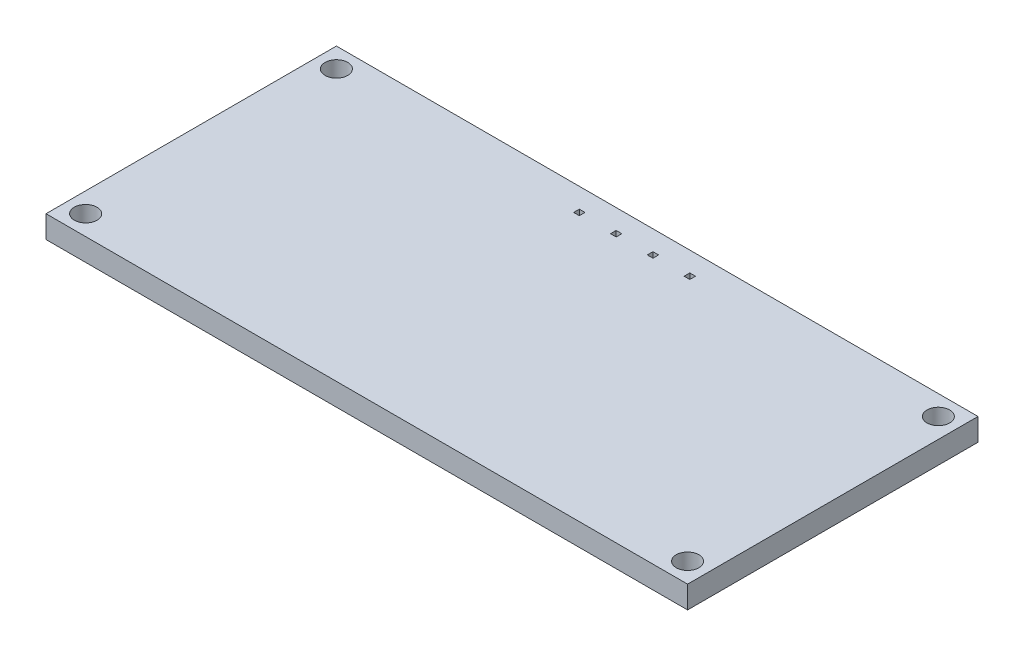
SolidWorks part; units mm, degrees
ref_plane "Alzado" through (0, 0, 0) normal (0, 0, 1) x (1, 0, 0)
ref_plane "Planta" through (0, 0, 0) normal (0, 1, 0) x (1, 0, 0)
ref_plane "Vista lateral" through (0, 0, 0) normal (1, 0, 0) x (0, 0, -1)
sketch "Croquis1" plane through (0, 0, 0) normal (0, 1, 0) x (1, 0, 0)
  line L1 (0, 0) -> (45.31, 0)
  line L2 (0, 0) -> (0, 20.51)
  line L3 (0, 20.51) -> (45.31, 20.51)
  line L4 (45.31, 0) -> (45.31, 20.51)
  circle A0 centre (1.4, 19.11) radius 0.8
  circle A1 centre (43.91, 19.11) radius 0.8
  circle A2 centre (1.4, 1.4) radius 0.8
  circle A3 centre (43.91, 1.4) radius 0.8
  point P13 (1.4, 19.91)
  point P14 (0.6, 19.11)
  point P15 (43.91, 0.6)
  point P16 (0, 0)
  point P17 (0, 0)
  point P19 (44.71, 19.11)
  dimension "D3" = 1.6
  dimension "D1" = 45.31
  dimension "D2" = 20.51
  dimension "D4" = 0.6
  dimension "D5" = 0.6
  dimension "D6" = 0.6
  dimension "D7" = 0.6
extrude "Saliente-Extruir1" add sketch "Croquis1" along normal blind 1.58
sketch "Croquis2" plane through (0, 0, 0) normal (0, -1, 0) x (1, 0, 0)
  line L0 (21.555, -18.71) -> (21.555, -19.11)
  line L1 (18.555, -18.71) -> (18.955, -18.71)
  line L2 (18.555, -18.71) -> (18.555, -19.11)
  line L3 (18.555, -19.11) -> (18.955, -19.11)
  line L4 (18.955, -18.71) -> (18.955, -19.11)
  line L5 (21.155, -18.71) -> (21.155, -19.11)
  line L6 (21.155, -18.71) -> (21.555, -18.71)
  line L7 (21.155, -19.11) -> (21.555, -19.11)
  line L8 (24.155, -18.71) -> (24.155, -19.11)
  line L9 (23.755, -18.71) -> (23.755, -19.11)
  line L10 (23.755, -18.71) -> (24.155, -18.71)
  line L11 (23.755, -19.11) -> (24.155, -19.11)
  line L12 (26.755, -18.71) -> (26.755, -19.11)
  line L13 (26.355, -18.71) -> (26.355, -19.11)
  line L14 (26.355, -18.71) -> (26.755, -18.71)
  line L15 (26.355, -19.11) -> (26.755, -19.11)
  line L16 (18.555, -18.71) -> (26.755, -18.71) construction
  line L17 (45.31, -20.51) -> (0, -20.51) construction
  point P5 (22.655, -18.71)
  point P17 (22.655, -20.51)
  point P18 (0, 0)
  point P21 (0, 0)
  dimension "D1" = 0.4
  dimension "D3" = 1.4
  dimension "D4" = 2.2
  dimension "D2" = 4
extrude "Cortar-Extruir1" cut sketch "Croquis2" against normal through all
